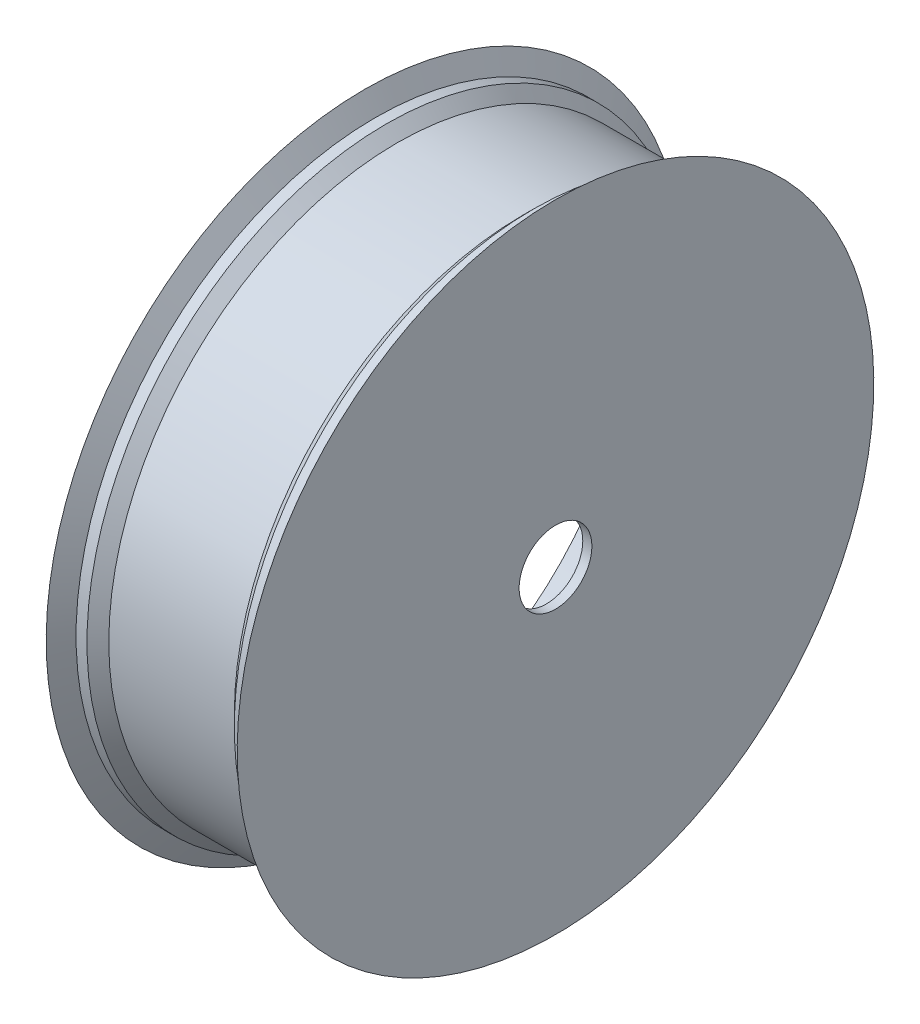
SolidWorks part; units mm, degrees
material "Plain Carbon Steel"
ref_plane "Front Plane" through (0, 0, 0) normal (0, 0, 1) x (1, 0, 0)
ref_plane "Top Plane" through (0, 0, 0) normal (0, 1, 0) x (1, 0, 0)
ref_plane "Right Plane" through (0, 0, 0) normal (1, 0, 0) x (0, 0, -1)
sketch "Sketch1" plane through (0, 0, 0) normal (0, 0, 1) x (1, 0, 0)
  line L0 (0, 0) -> (0, 350)
  line L2 (210, 350) -> (210, 0)
  line L3 (210, 0) -> (0, 0)
  line L6 (210, 350) -> (198, 329.1693)
  line L7 (198, 329.1693) -> (186, 329.1693)
  line L8 (186, 329.1693) -> (174, 317.1693)
  line L9 (0, 350) -> (12, 329.1693)
  line L10 (174, 317.1693) -> (36, 317.1693)
  line L11 (12, 329.1693) -> (24, 329.1693)
  line L12 (24, 329.1693) -> (36, 317.1693)
  point P15 (105, 317.1693)
  dimension "D1" = 350
  dimension "D2" = 210
  dimension "D3" = 12
  dimension "D4" = 12
  dimension "D5" = 12
  dimension "D6" = 138
revolve "Revolve2" add sketch "Sketch1" angle 360 about L3
sketch "Sketch2" plane through (0, 0, 0) normal (-1, 0, 0) x (0, 0, 1)
  circle A0 centre (0, 0) radius 300
extrude "Cut-Extrude1" cut sketch "Sketch2" against normal blind 200 contours A0
sketch "Sketch3" plane through (210, 0, 0) normal (1, 0, 0) x (0, 0, -1)
  circle A0 centre (0, 0) radius 40
extrude "Cut-Extrude2" cut sketch "Sketch3" against normal blind 200
